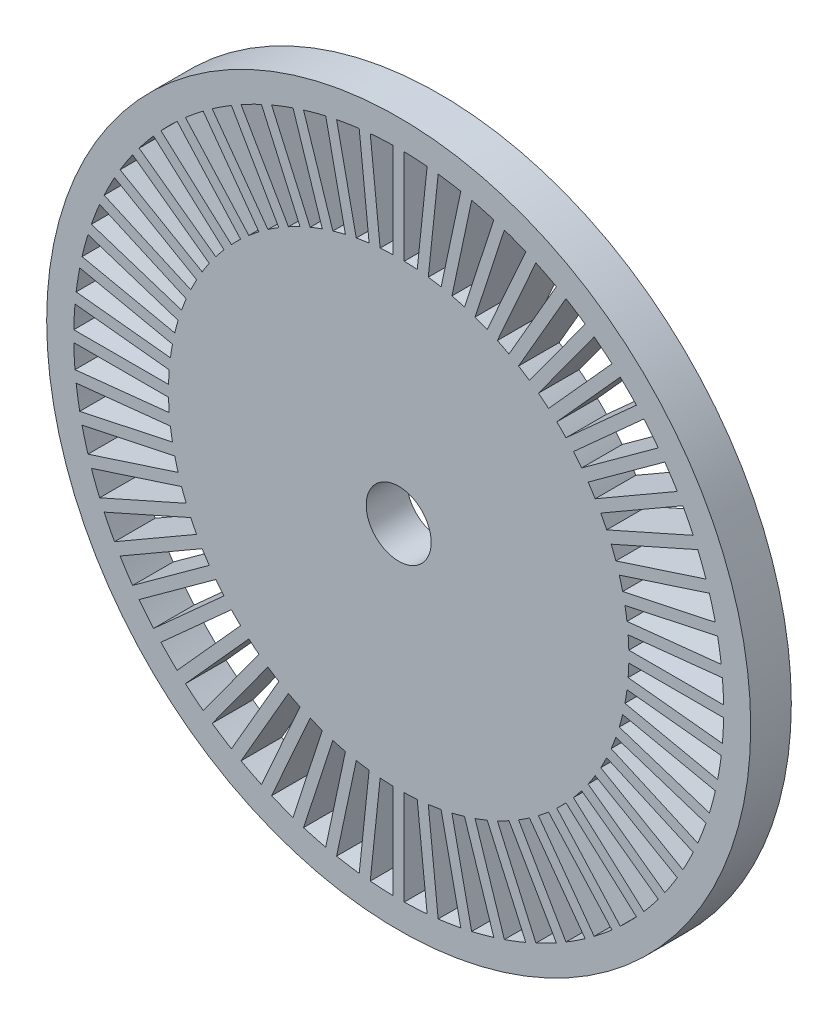
SolidWorks part; units mm, degrees
ref_plane "Płaszczyzna przednia" through (0, 0, 0) normal (0, 0, 1) x (1, 0, 0)
ref_plane "Płaszczyzna górna" through (0, 0, 0) normal (0, 1, 0) x (1, 0, 0)
ref_plane "Płaszczyzna prawa" through (0, 0, 0) normal (1, 0, 0) x (0, 0, -1)
sketch "Szkic1" plane through (0, 0, 0) normal (0, 0, 1) x (1, 0, 0)
  circle A0 centre (0, 0) radius 13
  circle A1 centre (0, 0) radius 1.2
  dimension "D1" = 26
  dimension "D2" = 2.4
extrude "Dodanie-wyciągnięcie1" add sketch "Szkic1" along normal blind 1.5
sketch "Szkic2" plane through (0, 0, 0) normal (0, 0, -1) x (-1, 0, 0)
  circle A0 centre (0, 0) radius 12
  circle A1 centre (0, 0) radius 8.5
  dimension "D1" = 24
  dimension "D2" = 17
extrude "Wytnij-wyciągnięcie1" cut sketch "Szkic2" against normal up to surface (1.5 mm away) up to face at (13, 0, 1.5)
sketch "Szkic3" plane through (0, 0, 1.5) normal (0, 0, 1) x (1, 0, 0)
  line L0 (0, 0) -> (0, 12.5303) construction
  line L2 (-0.205, 12.2975) -> (0.205, 12.2975)
  line L3 (-0.205, 12.2975) -> (-0.205, 8.1438)
  line L4 (-0.205, 8.1438) -> (0.205, 8.1438)
  line L5 (0.205, 12.2975) -> (0.205, 8.1438)
  line L6 (-0.205, 12.2975) -> (0.205, 8.1438) construction
  line L7 (-0.205, 8.1438) -> (0.205, 12.2975) construction
  point P3 (0, 10.2206)
  dimension "D1" = 0.41
extrude "Dodanie-wyciągnięcie2" add sketch "Szkic3" against normal up to surface (1.5 mm away) up to face at (1.2, 0, 0)
pattern_circular "Szyk kołowy1" count 60 every 6 about axis through (0, 0, 0) along (0, 0, 1) of "Dodanie-wyciągnięcie2"
